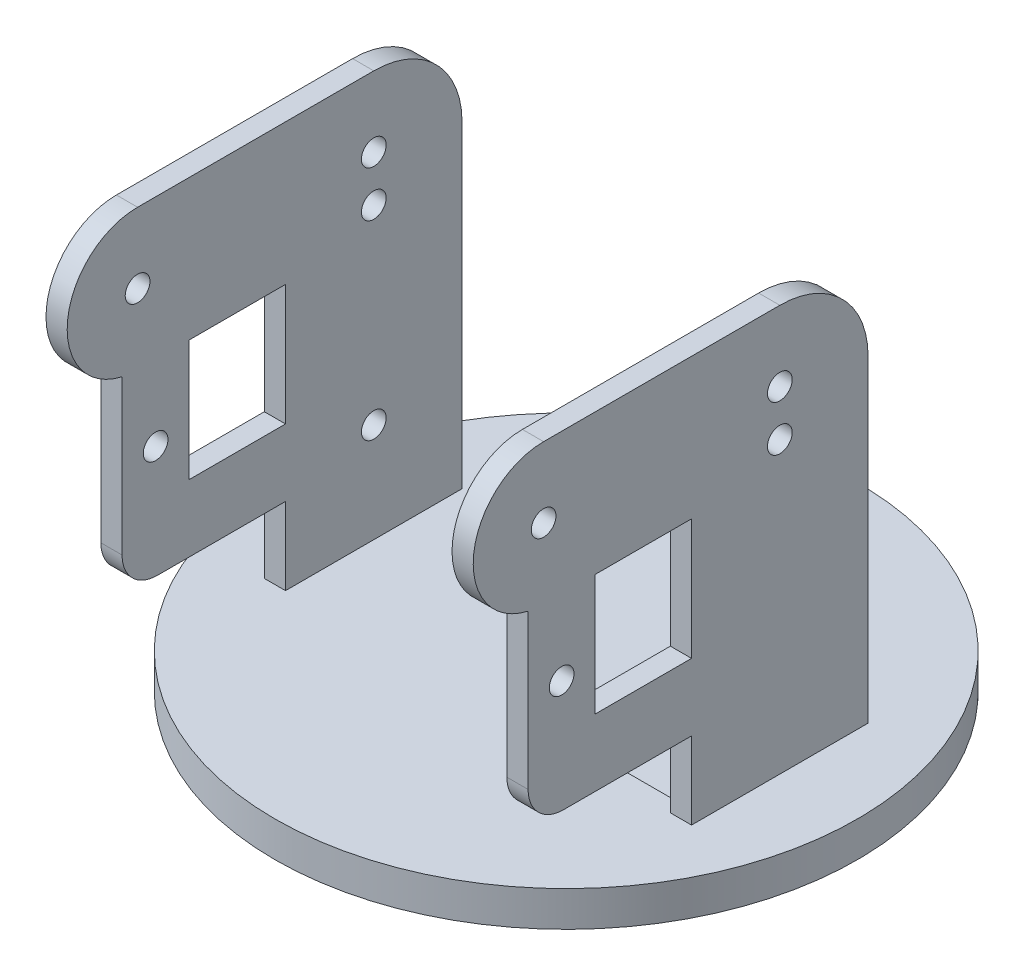
SolidWorks part; units mm, degrees
ref_plane "Plan de face" through (0, 0, 0) normal (0, 0, 1) x (1, 0, 0)
ref_plane "Plan de dessus" through (0, 0, 0) normal (0, 1, 0) x (1, 0, 0)
ref_plane "Plan de droite" through (0, 0, 0) normal (1, 0, 0) x (0, 0, -1)
sketch "Esquisse1" plane through (0, 0, 0) normal (0, 1, 0) x (1, 0, 0)
  circle A0 centre (0, 0) radius 50.5
  dimension "D1" = 101
extrude "Boss.-Extru.1" add sketch "Esquisse1" along normal blind 15
sketch "Esquisse2" plane through (0, 15, 0) normal (0, 1, 0) x (1, 0, 0)
  circle A0 centre (0, 0) radius 82.5
  dimension "D1" = 165
extrude "Boss.-Extru.2" add sketch "Esquisse2" along normal blind 10
sketch "Esquisse3" plane through (0, 25, 0) normal (0, 1, 0) x (1, 0, 0)
  line L0 (0, 0) -> (54.5, 0) construction
  line L2 (14, 21.25) -> (54.5, 21.25)
  line L3 (14, 21.25) -> (14, -21.25)
  line L4 (14, -21.25) -> (54.5, -21.25)
  line L5 (54.5, 21.25) -> (54.5, -21.25)
  dimension "D1" = 42.5
  dimension "D2" = 40.5
  dimension "D3" = 54.5
extrude "Enlèv. mat.-Extru.1" cut sketch "Esquisse3" against normal blind 2
sketch "Esquisse4" plane through (0, 23, 0) normal (0, 1, 0) x (1, 0, 0)
  line L0 (54.5, -21.25) -> (54.5, 21.25) construction
  line L1 (44.5, 8) -> (54.5, 8)
  line L2 (44.5, 8) -> (44.5, -8)
  line L3 (44.5, -8) -> (54.5, -8)
  line L4 (54.5, 8) -> (54.5, -8)
  line L5 (0, 0) -> (20.6005, 0) construction
  dimension "D1" = 16
  dimension "D2" = 10
extrude "Enlèv. mat.-Extru.2" cut sketch "Esquisse4" against normal blind 6.3
sketch "Esquisse5" plane through (54.5, 0, 0) normal (-1, 0, 0) x (0, 0, 1)
  line L0 (21.25, 25) -> (-21.25, 25) construction
  line L1 (-25, 25) -> (25, 25)
  line L2 (-25, 25) -> (-25, 115)
  line L3 (-25, 115) -> (25, 115)
  line L4 (25, 25) -> (25, 115)
  line L5 (21.25, 25) -> (-21.25, 25) construction
  line L6 (0, 0) -> (0, 40.8021) construction
  line L7 (-50.5, 0) -> (50.5, 0) construction
  arc A0 (25, 115) -> (-25, 115) centre (0, 115) ccw
  line M6 (21.25, 25) -> (-21.25, 25)
  dimension "D1" = 90
  dimension "D2" = 50
extrude "Boss.-Extru.3" add sketch "Esquisse5" against normal blind 6 contours L4 L3 L2 M6 | L3 A0
mirror "Symétrie1" about plane through (0, 0, 0) normal (1, 0, 0) of "Boss.-Extru.3"
sketch "Esquisse6" plane through (54.5, 0, 0) normal (-1, 0, 0) x (0, 0, 1)
  line L1 (0, 140) -> (66.9, 140)
  line L2 (0, 140) -> (0, 100.1264)
  line L3 (0, 100.1264) -> (66.9, 100.1264)
  line L4 (66.9, 140) -> (66.9, 100.1264)
  line L5 (0, 131.472) -> (0, 45.1628) construction
  line L6 (66.9, 120.0632) -> (0, 120.0632) construction
  arc A0 (25, 115) -> (-25, 115) centre (0, 115) ccw construction
  arc A1 (66.9, 100.1264) -> (66.9, 140) centre (66.9, 120.0632) ccw
  line M9 (25, 25) -> (25, 115)
  arc M10 (25, 115) -> (-25, 115) centre (0, 115) ccw
  dimension "D1" = 66.9
extrude "Boss.-Extru.4" add sketch "Esquisse6" against normal up to surface (6 mm away) contours L4 L1 L3 M10 M9 | L4 A1 up to face at (60.5, 76.25, 0)
sketch "Esquisse7" plane through (60.5, 0, 0) normal (1, 0, 0) x (0, 0, -1)
  circle A0 centre (-66.9, 120.0632) radius 3.5
  dimension "D1" = 7
extrude "Enlèv. mat.-Extru.3" cut sketch "Esquisse7" against normal blind 10
sketch "Esquisse8" plane through (60.5, 0, 0) normal (1, 0, 0) x (0, 0, -1)
  line L0 (-66.9, 120.0632) -> (0, 120.0632) construction
  line L1 (0, 0) -> (0, 58.5616) construction
  line L2 (-50.5, 0) -> (50.5, 0) construction
  circle A0 centre (0, 120.0632) radius 3.5
  circle A2 centre (-66.9, 120.0632) radius 3.5 construction
  dimension "D2" = 7
  dimension "D1" = 66.9
extrude "Enlèv. mat.-Extru.4" cut sketch "Esquisse8" against normal up to surface (6 mm away) up to face at (54.5, 120.0632, 63.4)
sketch "Esquisse9" plane through (-60.5, 0, 0) normal (-1, 0, 0) x (0, 0, 1)
  line L0 (0, 140) -> (66.9, 140) construction
  line L1 (25, 100.1264) -> (66.9, 100.1264) construction
  line L2 (0, 140) -> (66.9, 140)
  line L3 (25, 100.1264) -> (66.9, 100.1264)
  line L5 (25, 115) -> (25, 100.1264)
  arc A0 (25, 115) -> (-25, 115) centre (0, 115) ccw construction
  circle A1 centre (66.9, 120.0632) radius 3.5 construction
  arc A2 (66.9, 100.1264) -> (66.9, 140) centre (66.9, 120.0632) ccw construction
  arc A3 (25, 115) -> (0, 140) centre (0, 115) ccw
  circle A4 centre (66.9, 120.0632) radius 3.5
  arc A5 (66.9, 100.1264) -> (66.9, 140) centre (66.9, 120.0632) ccw
extrude "Boss.-Extru.5" add sketch "Esquisse9" against normal up to surface (6 mm away) up to face at (-54.5, 76.25, 0)
sketch "Esquisse10" plane through (-60.5, 0, 0) normal (-1, 0, 0) x (0, 0, 1)
  line L0 (66.9, 120.0632) -> (-5.8896, 120.0632) construction
  circle A1 centre (0, 120.0632) radius 3.5
  dimension "D1" = 7
extrude "Enlèv. mat.-Extru.5" cut sketch "Esquisse10" against normal up to surface (6 mm away) up to face at (-54.5, 92.9187, 21.2227)
sketch "Esquisse13" plane through (-60.5, 0, 0) normal (-1, 0, 0) x (0, 0, 1)
  line L0 (0, 120.0632) -> (0, 53.1632) construction
  circle A2 centre (0, 53.1632) radius 3.5
  dimension "D1" = 66.9
  dimension "D3" = 7
extrude "Enlèv. mat.-Extru.6" cut sketch "Esquisse13" against normal blind 10 contours A2
sketch "Esquisse17" plane through (-60.5, 0, 0) normal (-1, 0, 0) x (0, 0, 1)
  line L0 (0, 120.0632) -> (0, 53.1632) construction
  circle A0 centre (0, 120.0632) radius 50 construction
  circle A3 centre (61.6611, 78.3131) radius 50 construction
  circle A4 centre (32.0398, 62.7734) radius 33.45 construction
  circle A5 centre (0, 53.1632) radius 20 construction
  circle A6 centre (0, 107.0851) radius 20 construction
  circle A7 centre (0, 107.0851) radius 3.5
  dimension "D1" = 100
  dimension "D2" = 66.9
  dimension "D3" = 100
  dimension "D4" = 40
  dimension "D5" = 40
  dimension "D6" = 7
extrude "Enlèv. mat.-Extru.7" cut sketch "Esquisse17" against normal up to surface (6 mm away) up to face at (-54.5, 53.1632, -3.5)
sketch "Esquisse19" plane through (-60.5, 0, 0) normal (-1, 0, 0) x (0, 0, 1)
  line L0 (0, 120.0632) -> (0, 53.1632) construction
  line L1 (25, 46.8887) -> (71.295, 46.8887)
  line L2 (25, 25) -> (25, 100.1264) construction
  line L3 (71.295, 46.8887) -> (71.295, 100.6169)
  line L4 (52.295, 100.1264) -> (52.295, 65.8887)
  line L5 (25, 100.1264) -> (66.9, 100.1264) construction
  line L6 (52.295, 65.8887) -> (25, 65.8887)
  line L7 (25, 65.8887) -> (25, 46.8887)
  line L8 (52.295, 100.1264) -> (66.9, 100.1264)
  line L9 (61.795, 107.0851) -> (61.795, 44.6183) construction
  circle A0 centre (0, 120.0632) radius 50 construction
  circle A1 centre (61.795, 78.7942) radius 50 construction
  circle A2 centre (30.9349, 65.8887) radius 33.45 construction
  circle A3 centre (0, 53.1632) radius 20 construction
  circle A5 centre (0, 61.4061) radius 3.5
  circle A6 centre (0, 53.1632) radius 3.5 construction
  circle A7 centre (0, 120.0632) radius 3.5 construction
  circle A8 centre (0, 107.0851) radius 20 construction
  arc A10 (66.9, 100.1264) -> (66.9, 140) centre (66.9, 120.0632) ccw construction
  arc A11 (66.9, 100.1264) -> (71.295, 100.6169) centre (66.9, 120.0632) ccw
  circle A12 centre (61.795, 78.7942) radius 3.5
  dimension "D1" = 100
  dimension "D2" = 100
  dimension "D3" = 40
  dimension "D4" = 40
  dimension "D5" = 66.9
  dimension "D6" = 7
  dimension "D7" = 19
  dimension "D8" = 19
extrude "Boss.-Extru.8" add sketch "Esquisse19" against normal blind 6
fillet "Congé1" radius 10 1 edges at (-57.5, 46.8887, 71.295)
mirror "Symétrie4" about plane through (0, 0, 0) normal (1, 0, 0) of "Congé1", "Boss.-Extru.8", "Enlèv. mat.-Extru.7"
